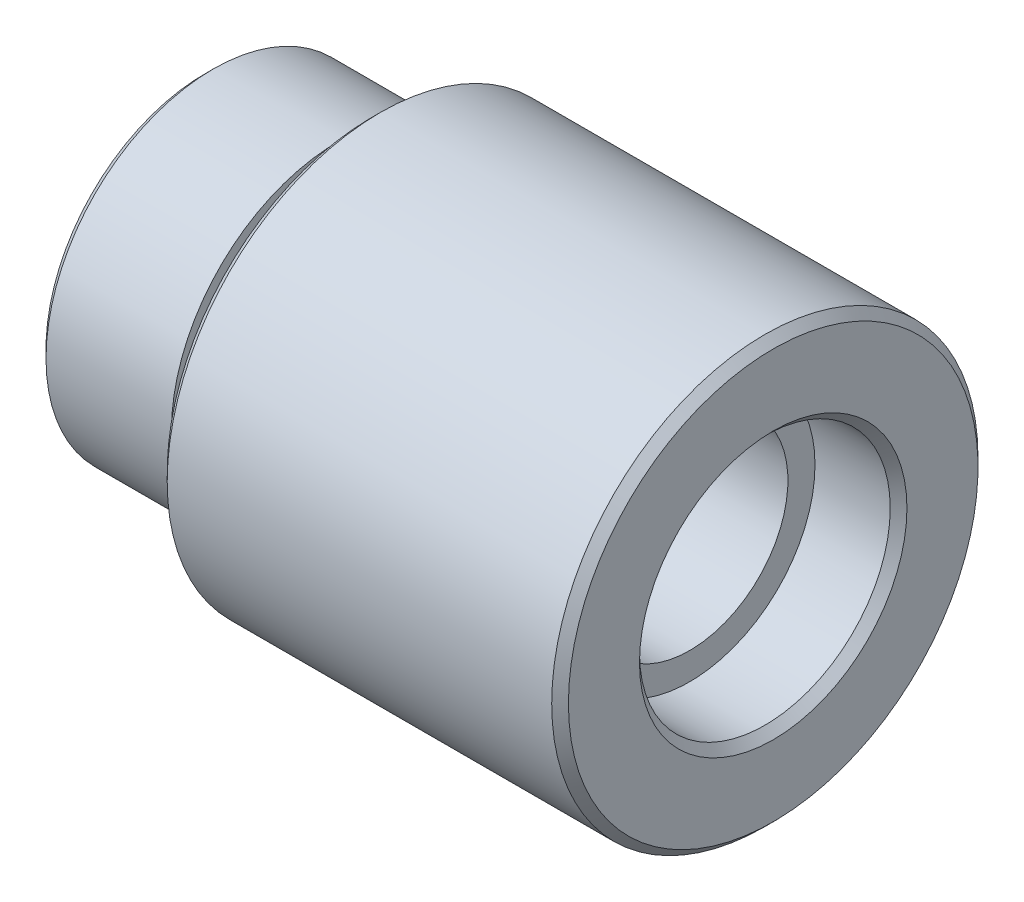
SolidWorks part; units mm, degrees
ref_plane "Plan1" through (0, 0, 0) normal (0, 0, 1) x (1, 0, 0)
ref_plane "Plan2" through (0, 0, 0) normal (0, 1, 0) x (1, 0, 0)
ref_plane "Plan3" through (0, 0, 0) normal (1, 0, 0) x (0, 0, -1)
sketch "Esquisse1" plane through (0, 0, 0) normal (0, 0, 1) x (1, 0, 0)
  line L0 (0, 0) -> (50, 0) construction
  line L1 (0, 7.5) -> (5, 7.5)
  line L2 (34, 7.5) -> (34, 12.75)
  line L3 (34, 12.75) -> (10, 12.75)
  line L4 (10, 12.75) -> (10, 9.25)
  line L5 (10, 9.25) -> (8, 9.25)
  line L6 (8, 9.25) -> (8, 10)
  line L7 (8, 10) -> (0, 10)
  line L8 (0, 10) -> (0, 7.5)
  line L9 (5, 7.5) -> (5, 5.88)
  line L10 (5, 5.88) -> (29, 5.88)
  line L11 (29, 5.88) -> (29, 7.5)
  line L12 (29, 7.5) -> (34, 7.5)
  dimension "D1" = 12.75
  dimension "D2" = 9.25
  dimension "D3" = 10
  dimension "D4" = 34
  dimension "D5" = 24
  dimension "D6" = 8
  dimension "D7" = 7.5
  dimension "D8" = 5.88
  dimension "D9" = 5
  dimension "D10" = 5
revolve "Base-Révolution" add sketch "Esquisse1"
cosmetic thread "Représentation de filetage2"
chamfer "Chanfrein1" distance 0.5 angle 45 5 edges at (10, 0, 12.75) (0, 0, 10) (0, 0, 7.5) (34, 0, 7.5) (34, 0, 12.75)
sketch "Esquisse2" plane through (0, 0, 0) normal (0, 0, 1) x (1, 0, 0)
  line L4 (29, 0) -> (5, 0) construction
  point P6 (17, 0)
